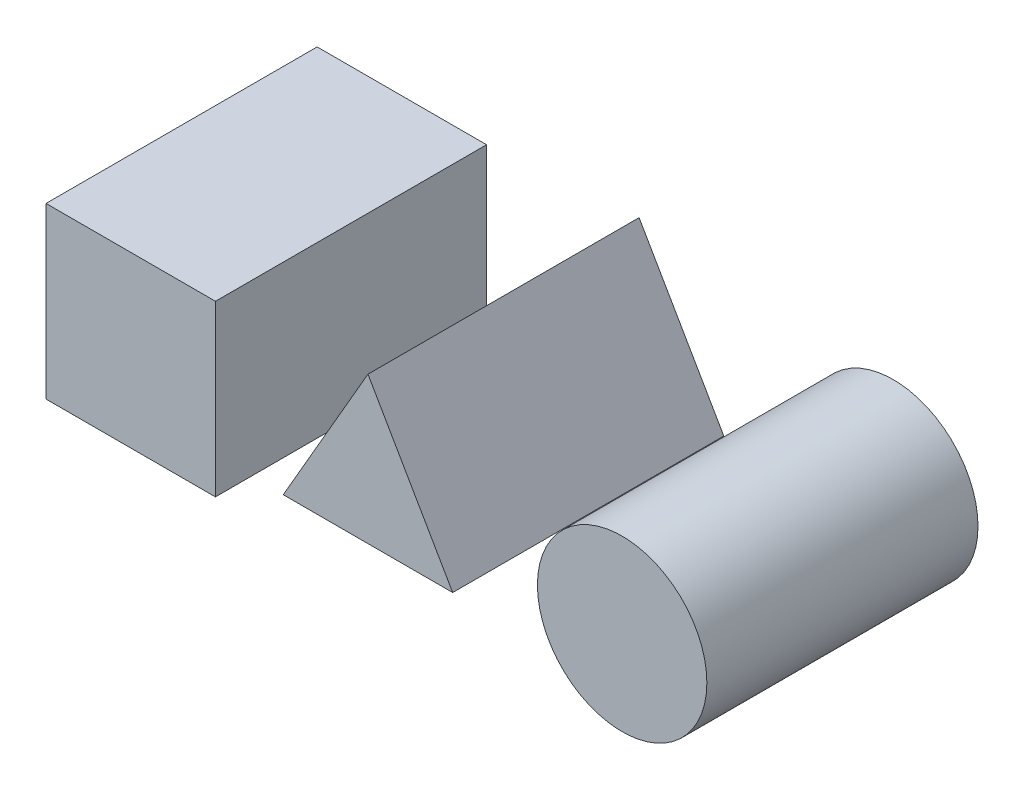
SolidWorks part; units mm, degrees
ref_plane "Front Plane" through (0, 0, 0) normal (0, 0, 1) x (1, 0, 0)
ref_plane "Top Plane" through (0, 0, 0) normal (0, 1, 0) x (1, 0, 0)
ref_plane "Right Plane" through (0, 0, 0) normal (1, 0, 0) x (0, 0, -1)
sketch "Sketch1" plane through (0, 0, 0) normal (0, 0, 1) x (1, 0, 0)
  line L0 (-125, 0) -> (125, 0) construction
  line L1 (-125, 62.5) -> (125, 62.5)
  line L2 (-125, 62.5) -> (-125, -62.5)
  line L3 (-125, -62.5) -> (125, -62.5)
  line L4 (125, 62.5) -> (125, -62.5)
  line L5 (0, 62.5) -> (0, -62.5) construction
  line L6 (-25, -14.4338) -> (0, 28.8675)
  line L7 (-95, 25) -> (-45, 25)
  line L8 (-95, 25) -> (-95, -25)
  line L9 (-95, -25) -> (-45, -25)
  line L10 (-45, 25) -> (-45, -25)
  line L11 (-95, 25) -> (-45, -25) construction
  line L12 (-95, -25) -> (-45, 25) construction
  line L14 (-1.3522, 0) -> (0, -1.3522)
  line L18 (0, 28.8675) -> (25, -14.4338)
  line L19 (25, -14.4338) -> (-25, -14.4338)
  line L20 (-25, -14.4338) -> (12.5, 7.2169) construction
  line L21 (25, -14.4338) -> (-12.5, 7.2169) construction
  line L22 (0, 28.8675) -> (0, 0) construction
  circle A0 centre (75, 0) radius 25
  point P10 (-70, 0)
  point P20 (0, 0)
  point P27 (7.7505, -5.3087)
  point P28 (0, 0)
  dimension "D2" = 50
  dimension "cylinder" = 50
  dimension "D1" = 30
  dimension "square2" = 50
  dimension "square" = 50
  dimension "triangle3" = 50
  dimension "triangle2" = 50
  dimension "triangle" = 50
extrude "Boss-Extrude1" add sketch "Sketch1" along normal blind 80
